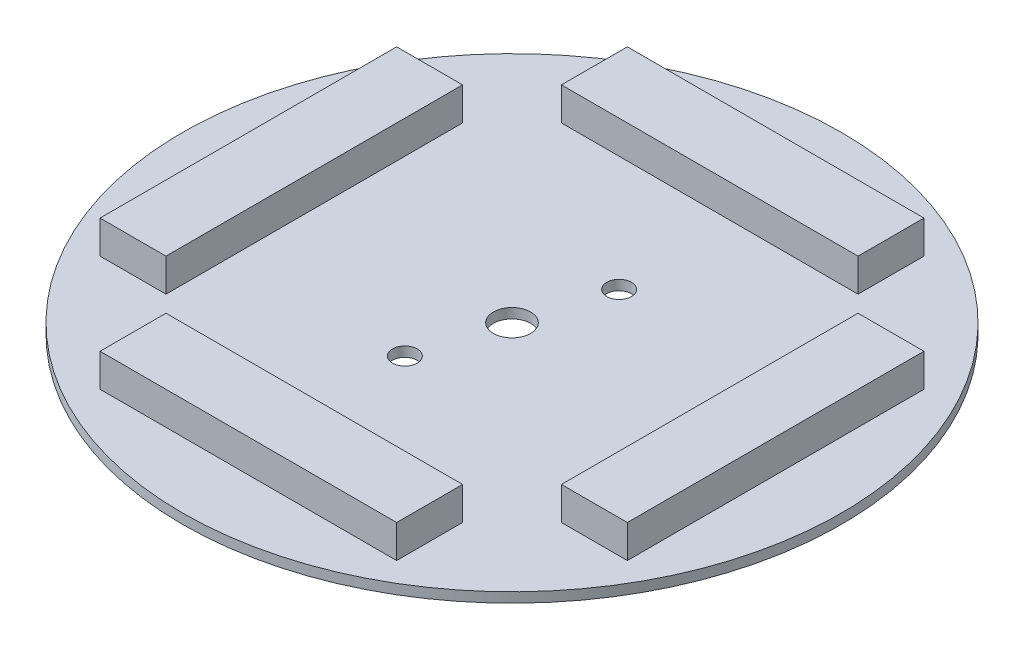
SolidWorks part; units mm, degrees
material "A-Glass Fiber"
ref_plane "Front Plane" through (0, 0, 0) normal (0, 0, 1) x (1, 0, 0)
ref_plane "Top Plane" through (0, 0, 0) normal (0, 1, 0) x (1, 0, 0)
ref_plane "Right Plane" through (0, 0, 0) normal (1, 0, 0) x (0, 0, -1)
sketch "Sketch1" plane through (0, 0, 0) normal (0, 1, 0) x (1, 0, 0)
  line L0 (1.5, 5) -> (0, 0) construction
  line L1 (0, 20) -> (0, -20) construction
  line L2 (0, 0) -> (-1.5, -5) construction
  circle A0 centre (0, 0) radius 20
  circle A1 centre (0, 0) radius 1.1303
  circle A2 centre (1.5, 5) radius 0.75
  circle A3 centre (-1.5, -5) radius 0.75
  dimension "D1" = 40
  dimension "D5" = 2.2606
  dimension "D6" = 1.5
  dimension "D7" = 1.5
  dimension "D2" = 1.5
  dimension "D3" = 5
  dimension "D4" = 5
extrude "PCB" add sketch "Sketch1" along normal blind 0.6 contours A0 | A3 | A1 | A2
sketch "Sketch2" plane through (0, 0.6, 0) normal (0, 1, 0) x (1, 0, 0)
  line L0 (0, 20) -> (0, 0) construction
  line L1 (-9, 16) -> (9, 16)
  line L2 (-9, 16) -> (-9, 12)
  line L3 (-9, 12) -> (9, 12)
  line L4 (9, 16) -> (9, 12)
  circle A0 centre (0, 0) radius 20 construction
  point P9 (0, 16)
  dimension "D1" = 4
  dimension "D2" = 18
  dimension "D3" = 16
extrude "Hirose Connector Stack" add sketch "Sketch2" along normal blind 2 contours L1 L4 L3 L2
pattern_circular "CirPattern1" count 4 over 360 about axis through (0, 0, 0) along (0, 1, 0) of "Hirose Connector Stack"
